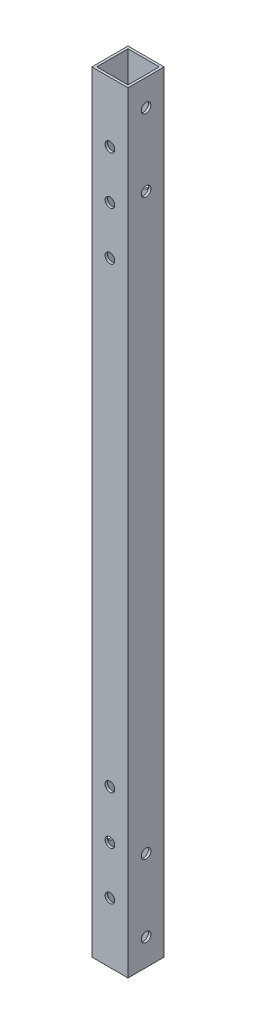
SolidWorks part; units mm, degrees
material "6061 合金"
ref_plane "Front" through (0, 0, 0) normal (0, 0, 1) x (1, 0, 0)
ref_plane "Top" through (0, 0, 0) normal (0, 1, 0) x (1, 0, 0)
ref_plane "Right" through (0, 0, 0) normal (1, 0, 0) x (0, 0, -1)
sketch "草图1" plane through (0, 0, 0) normal (0, 1, 0) x (1, 0, 0)
  line L1 (-7.5, -7.5) -> (7.5, -7.5)
  line L2 (-7.5, -7.5) -> (-7.5, 7.5)
  line L3 (-7.5, 7.5) -> (7.5, 7.5)
  line L4 (7.5, -7.5) -> (7.5, 7.5)
  line L5 (-7.5, -7.5) -> (7.5, 7.5) construction
  line L6 (-7.5, 7.5) -> (7.5, -7.5) construction
  line L7 (-6.5, -6.5) -> (6.5, -6.5)
  line L8 (-6.5, -6.5) -> (-6.5, 6.5)
  line L9 (-6.5, 6.5) -> (6.5, 6.5)
  line L10 (6.5, -6.5) -> (6.5, 6.5)
  line L11 (-6.5, -6.5) -> (6.5, 6.5) construction
  line L12 (-6.5, 6.5) -> (6.5, -6.5) construction
  point P0 (0, 0)
  point P5 (0, 0)
  dimension "D1" = 15
  dimension "D2" = 15
  dimension "D3" = 1
  dimension "D4" = 1
extrude "凸台-拉伸1" add sketch "草图1" along normal blind 320
sketch "草图3" plane through (0, 0, 7.5) normal (0, 0, 1) x (1, 0, 0)
  line L0 (0, 50) -> (0, -49950) construction
  line L1 (-7.5, 320) -> (7.5, 320) construction
  line L2 (5, 160) -> (-49995, 160) construction
  line L3 (7.5, 320) -> (7.5, 0) construction
  circle A0 centre (0, 295) radius 2
  circle A1 centre (0, 275) radius 2
  circle A2 centre (0, 45) radius 2
  circle A3 centre (0, 25) radius 2
  circle A4 centre (0, 255) radius 2
  circle A5 centre (0, 65) radius 2
  point P4 (0, 320)
  point P13 (7.5, 160)
  dimension "D1" = 4
  dimension "D2" = 4
  dimension "D5" = 4
  dimension "D3" = 20
  dimension "D4" = 25
  dimension "D6" = 20
extrude "切除-拉伸2" cut sketch "草图3" against normal through all
sketch "草图4" plane through (-7.5, 0, 0) normal (-1, 0, 0) x (0, 0, 1)
  line L0 (0, 0) -> (0, 50000) construction
  line L1 (-7.5, 0) -> (7.5, 0) construction
  line L2 (-7.5, 160) -> (49992.5, 160) construction
  line L3 (-7.5, 320) -> (-7.5, 0) construction
  line L4 (7.5, 320) -> (7.5, 0) construction
  circle A0 centre (0, 11) radius 2
  circle A1 centre (0, 41) radius 2
  circle A2 centre (0, 279) radius 2
  circle A3 centre (0, 309) radius 2
  point P13 (-7.5, 160)
  point P16 (7.5, 160)
  dimension "D1" = 4
  dimension "D2" = 4
  dimension "D3" = 11
  dimension "D4" = 30
extrude "切除-拉伸3" cut sketch "草图4" against normal through all
sketch "草图5" [suppressed] plane through (7.5, 0, 0) normal (1, 0, 0) x (0, 0, -1)
  circle A0 centre (0, 11) radius 2 construction
  circle A1 centre (0, 41) radius 2 construction
  circle A2 centre (0, 259) radius 2 construction
  circle A3 centre (0, 289) radius 2 construction
  circle A4 centre (0, 11) radius 2
  circle A5 centre (0, 41) radius 2
  circle A6 centre (0, 259) radius 2
  circle A7 centre (0, 289) radius 2
extrude "凸台-拉伸2" [suppressed] add sketch "草图5" against normal blind 1
ref_plane "基准面1" [suppressed] through (0, 0, 0) normal (-1, 0, 0) x (0, 0, 1)
mirror "镜向1" [suppressed] about plane through (0, 0, 0) normal (-1, 0, 0)
sketch "草图6" [suppressed] plane through (-7.5, 0, 0) normal (-1, 0, 0) x (0, 0, 1)
  line L0 (-7.5, 0) -> (7.5, 0) construction
  line L1 (7.5, 150) -> (-78.7867, 150) construction
  line L2 (7.5, 300) -> (7.5, 0) construction
  circle A0 centre (0, 16) radius 1.65
  circle A1 centre (0, 36) radius 1.65
  circle A2 centre (0, 284) radius 1.65
  circle A3 centre (0, 264) radius 1.65
  dimension "D1" = 20
  dimension "D2" = 16
  dimension "D3" = 3.3
extrude "切除-拉伸4" [suppressed] cut sketch "草图6" against normal through all
equation "\"3。3\"=3.01309"
